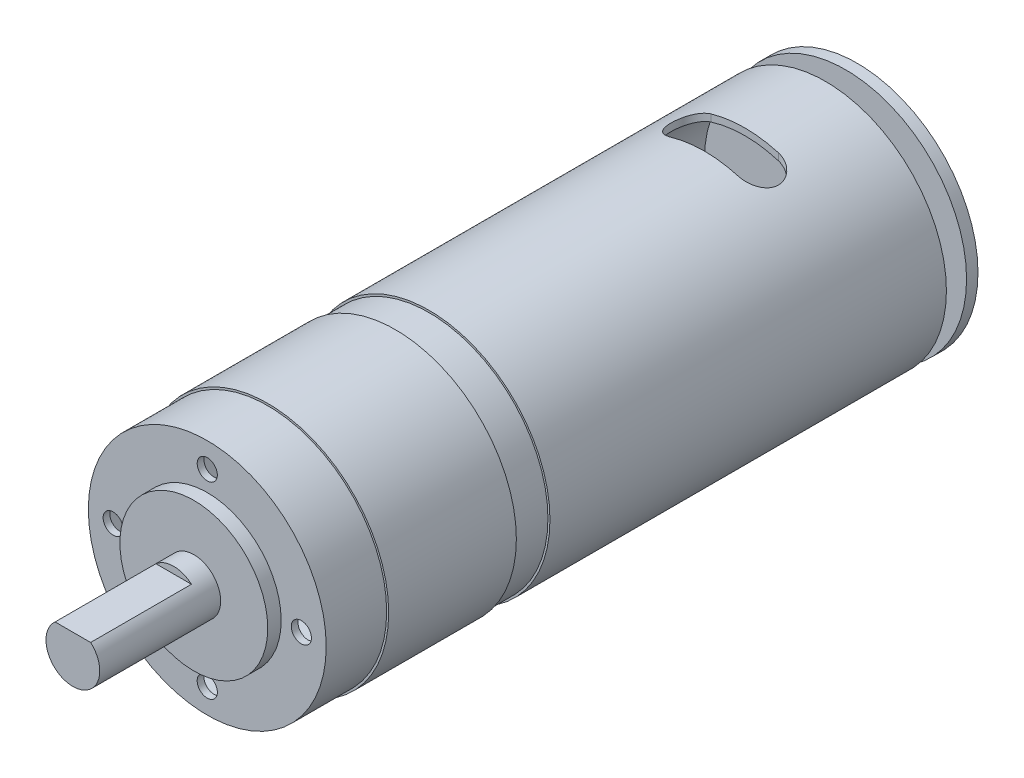
SolidWorks part; units mm, degrees
ref_plane "前视基准面" through (0, 0, 0) normal (0, 0, 1) x (1, 0, 0)
ref_plane "上视基准面" through (0, 0, 0) normal (0, 1, 0) x (1, 0, 0)
ref_plane "右视基准面" through (0, 0, 0) normal (1, 0, 0) x (0, 0, -1)
sketch "草图1" plane through (0, 0, 0) normal (0, 0, 1) x (1, 0, 0)
  circle A0 centre (0, 0) radius 18
  dimension "D1" = 36
extrude "凸台-拉伸1" add sketch "草图1" along normal blind 92
ref_plane "基准面1" through (0, 18, 0) normal (0, 1, 0) x (1, 0, 0)
sketch "草图7" plane through (0, 18, 0) normal (0, 1, 0) x (1, 0, 0)
  line L0 (0, 0) -> (0, -15)
  line L1 (-5, -15) -> (5, -15)
  line L2 (5, -15) -> (-5, -15) construction
  line L3 (5, -18) -> (-5, -18)
  line L4 (5, -12) -> (-5, -12)
  arc A0 (5, -18) -> (5, -12) centre (5, -15) ccw
  arc A1 (-5, -12) -> (-5, -18) centre (-5, -15) ccw
  point P5 (0, -15)
  dimension "D1" = 15
  dimension "D2" = 5
extrude "切除-拉伸2" cut sketch "草图7" against normal blind 36
shell "抽壳8" thickness 1
sketch "草图2" plane through (0, 0, 92) normal (0, 0, 1) x (1, 0, 0)
  circle A0 centre (0, 0) radius 11
  dimension "D1" = 22
extrude "凸台-拉伸2" add sketch "草图2" along normal blind 2
sketch "草图3" plane through (0, 0, 94) normal (0, 0, 1) x (1, 0, 0)
  circle A0 centre (0, 0) radius 4
  dimension "D1" = 8
extrude "凸台-拉伸3" add sketch "草图3" along normal blind 18
sketch "草图4" plane through (0, 0, 112) normal (0, 0, 1) x (1, 0, 0)
  line L0 (0, 4) -> (0, 3)
  line L1 (-2.6458, 3) -> (2.6458, 3)
  circle A0 centre (0, 0) radius 4
  circle M1 centre (0, 0) radius 4
  dimension "D2" = 8
  dimension "D1" = 1
extrude "切除-拉伸1" cut sketch "草图4" against normal blind 15 contours L0 L1 M1 | L1 L0 M1
sketch "草图5" plane through (0, 0, 0) normal (0, 0, -1) x (-1, 0, 0)
  circle A0 centre (0, 0) radius 5
  dimension "D1" = 10
extrude "凸台-拉伸4" add sketch "草图5" along normal blind 3
sketch "草图6" plane through (0, 0, -3) normal (0, 0, -1) x (-1, 0, 0)
  circle A0 centre (0, 0) radius 1.5
  dimension "D1" = 3
extrude "凸台-拉伸5" add sketch "草图6" along normal blind 9
fillet "圆角1" radius 1 1 edges at (-1.5, 0, -12)
sketch "草图8" plane through (0, 0, 92) normal (0, 0, 1) x (1, 0, 0)
  circle A0 centre (0, 0) radius 14
  circle A1 centre (14, 0) radius 1.5
  circle A2 centre (0, -14) radius 1.5
  circle A3 centre (-14, 0) radius 1.5
  circle A4 centre (0, 14) radius 1.5
  point P14 (0, 0)
  dimension "D1" = 28
  dimension "D2" = 3
  dimension "D3" = 4
extrude "切除-拉伸3" cut sketch "草图8" against normal blind 5 contours A0 A4 | A0 A4 | A0 A1 | A0 A1 | A3 | A2
sketch "草图9" plane through (0, 0, 0) normal (0, 1, 0) x (1, 0, 0)
  line L0 (0, 0) -> (0, -112) construction
  line L1 (-4, -112) -> (4, -112) construction
  line L2 (-18, -92) -> (18, -92) construction
  line L3 (18, -92) -> (17.7, -92)
  line L4 (18, -92) -> (18, -83)
  line L5 (18, -83) -> (17.7, -83)
  line L6 (17.7, -92) -> (17.7, -83)
  line L8 (18, -64) -> (17.7, -64)
  line L9 (18, -64) -> (18, -59)
  line L10 (18, -59) -> (17.7, -59)
  line L11 (17.7, -64) -> (17.7, -59)
  dimension "D1" = 0.3
  dimension "D2" = 0.3
  dimension "D3" = 9
  dimension "D4" = 19
  dimension "D5" = 5
revolve "切除-旋转1" cut sketch "草图9" angle 360 about L0
sketch "草图10" plane through (0, 0, -3) normal (0, 0, -1) x (-1, 0, 0)
  circle A0 centre (0, 0) radius 18
extrude "凸台-拉伸6" add sketch "草图10" along normal blind 1.7
ref_plane "基准面2" through (0, 0, -8.3) normal (0, 0, -1) x (-1, 0, 0)
sketch "草图12" plane through (0, 0, -8.3) normal (0, 0, -1) x (-1, 0, 0)
  circle A0 centre (0, 0) radius 7.5
  dimension "D1" = 15
extrude "凸台-拉伸7" add sketch "草图12" along normal mid plane 3
